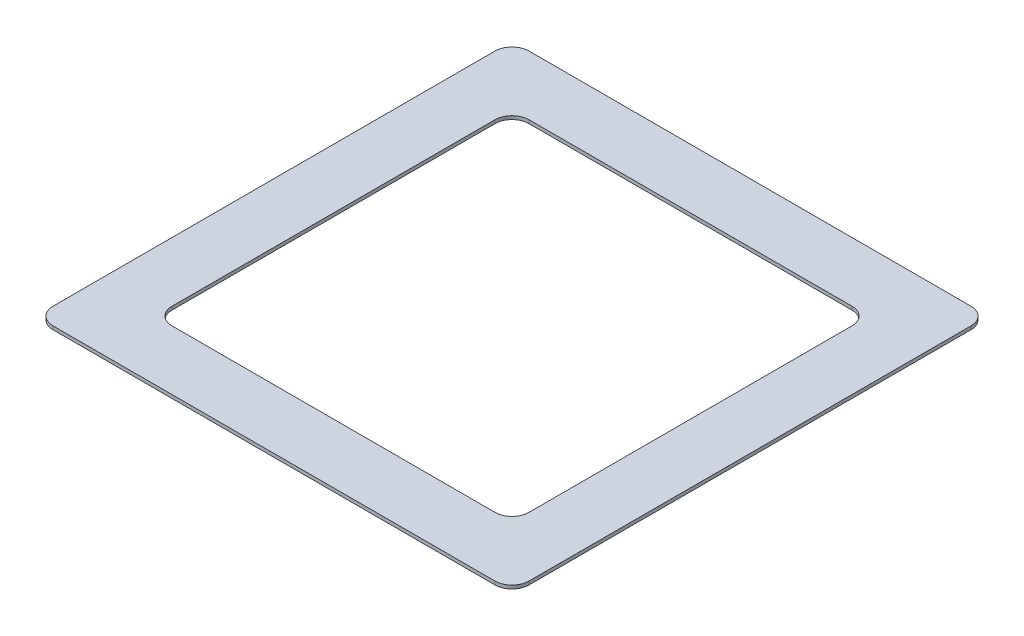
SolidWorks part; units mm, degrees
ref_plane "前视基准面" through (0, 0, 0) normal (0, 0, 1) x (1, 0, 0)
ref_plane "上视基准面" through (0, 0, 0) normal (0, 1, 0) x (1, 0, 0)
ref_plane "右视基准面" through (0, 0, 0) normal (1, 0, 0) x (0, 0, -1)
sketch "草图1" plane through (0, 0, 0) normal (0, 1, 0) x (1, 0, 0)
  line L0 (45, -35) -> (235, -35)
  line L1 (10, 0) -> (270, 0)
  line L2 (0, -10) -> (0, -270)
  line L3 (10, -280) -> (270, -280)
  line L4 (280, -10) -> (280, -270)
  line L5 (245, -45) -> (245, -235)
  line L6 (45, -245) -> (235, -245)
  line L7 (35, -45) -> (35, -235)
  line L8 (35, -35) -> (35, -245) construction
  line L9 (35, -245) -> (245, -245) construction
  line L10 (245, -35) -> (245, -245) construction
  line L11 (35, -35) -> (245, -35) construction
  arc A0 (0, -270) -> (10, -280) centre (10, -270) ccw
  arc A1 (270, -280) -> (280, -270) centre (270, -270) ccw
  arc A2 (270, 0) -> (280, -10) centre (270, -10) cw
  arc A3 (10, 0) -> (0, -10) centre (10, -10) ccw
  arc A4 (35, -45) -> (45, -35) centre (45, -45) cw
  arc A5 (245, -45) -> (235, -35) centre (235, -45) ccw
  arc A6 (235, -245) -> (245, -235) centre (235, -235) ccw
  arc A8 (35, -235) -> (45, -245) centre (45, -235) ccw
  arc A9 (35, -245) -> (35, -245) centre (35, -245) ccw construction
  arc A10 (245, -245) -> (245, -245) centre (245, -245) ccw construction
  arc A11 (245, -35) -> (245, -35) centre (245, -35) cw construction
  arc A12 (35, -35) -> (35, -35) centre (35, -35) ccw construction
  point P7 (0, -280)
  point P12 (280, 0)
  point P15 (0, 0)
  dimension "D3" = 10
  dimension "D5" = 10
  dimension "D1" = 280
  dimension "D2" = 280
  dimension "D4" = 35
extrude "凸台-拉伸1" add sketch "草图1" along normal blind 2
